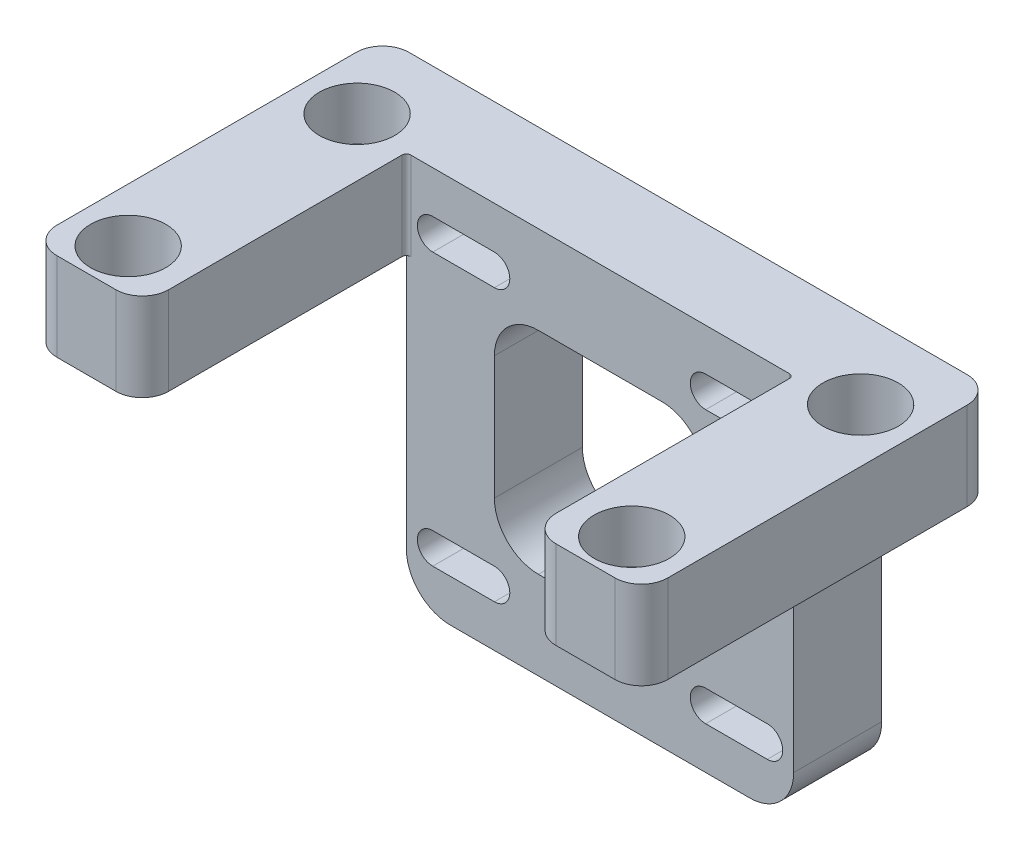
SolidWorks part; units mm, degrees
ref_plane "Front Plane" through (0, 0, 0) normal (0, 0, 1) x (1, 0, 0)
ref_plane "Top Plane" through (0, 0, 0) normal (0, 1, 0) x (1, 0, 0)
ref_plane "Right Plane" through (0, 0, 0) normal (1, 0, 0) x (0, 0, -1)
sketch "Sketch1" plane through (0, 0, 0) normal (0, 0, 1) x (1, 0, 0)
  line L0 (-19, 15.45) -> (-10.25, 15.45) construction
  line L1 (-22, 22) -> (22, 22)
  line L2 (-22, 22) -> (-22, -22)
  line L3 (-22, -22) -> (22, -22)
  line L4 (22, 22) -> (22, -22)
  line L5 (-22, 22) -> (22, -22) construction
  line L6 (-22, -22) -> (22, 22) construction
  line L7 (7, 12) -> (-7, 12)
  line L8 (12, 7) -> (12, -7)
  line L9 (7, -12) -> (-7, -12)
  line L10 (-12, 7) -> (-12, -7)
  line L11 (12, 12) -> (-12, -12) construction
  line L12 (12, -12) -> (-12, 12) construction
  line L13 (-19, 17.2) -> (-12, 17.2)
  line L14 (-19, 13.7) -> (-12, 13.7)
  line L15 (0, 0) -> (50000, 0) construction
  line L16 (-19, -17.2) -> (-12, -17.2)
  line L19 (12, 17.2) -> (19, 17.2)
  line L20 (12, 13.7) -> (19, 13.7)
  line L21 (10.25, 15.45) -> (19, 15.45) construction
  line L22 (-19, -13.7) -> (-12, -13.7)
  line L23 (12, -13.7) -> (19, -13.7)
  line L24 (12, -17.2) -> (19, -17.2)
  arc A0 (-12, -7) -> (-7, -12) centre (-7, -7) ccw
  arc A1 (7, -12) -> (12, -7) centre (7, -7) ccw
  arc A2 (12, 7) -> (7, 12) centre (7, 7) ccw
  arc A3 (-7, 12) -> (-12, 7) centre (-7, 7) ccw
  arc A4 (-19, 17.2) -> (-19, 13.7) centre (-19, 15.45) ccw
  arc A5 (19, 13.7) -> (19, 17.2) centre (19, 15.45) ccw
  circle A8 centre (0, 0) radius 12 construction
  arc A9 (12, 17.2) -> (12, 13.7) centre (12, 15.45) ccw
  arc A10 (-12, 17.2) -> (-12, 13.7) centre (-12, 15.45) cw
  arc A11 (-19, -17.2) -> (-19, -13.7) centre (-19, -15.45) cw
  arc A12 (-12, -17.2) -> (-12, -13.7) centre (-12, -15.45) ccw
  arc A13 (12, -17.2) -> (12, -13.7) centre (12, -15.45) cw
  arc A14 (19, -13.7) -> (19, -17.2) centre (19, -15.45) cw
  point P0 (0, 0)
  point P6 (0, 0)
  dimension "D4" = 5
  dimension "D9" = 1.75
  dimension "D1" = 44
  dimension "D2" = 44
  dimension "D3" = 24
  dimension "D5" = 38
  dimension "D6" = 1.75
  dimension "D7" = 15.45
  dimension "D8" = 7
extrude "Boss-Extrude1" add sketch "Sketch1" along normal blind 10
sketch "Sketch2" plane through (22, 0, 0) normal (1, 0, 0) x (0, 0, -1)
  line L0 (0, 12) -> (-40, 12)
  line L1 (0, -22) -> (0, 22) construction
  line L2 (0, 12) -> (0, 22)
  line L3 (0, 22) -> (-10, 22)
  line L4 (-40, 12) -> (-40, 16)
  line L5 (-40, 16) -> (0, 16) construction
  line L6 (-10, 22) -> (-40, 22)
  line L7 (-40, 22) -> (-40, 16)
  dimension "D1" = 4
  dimension "D2" = 40
  dimension "D3" = 12
extrude "Boss-Extrude2" add sketch "Sketch2" along normal blind 12.7
sketch "Sketch3" plane through (0, 12, 0) normal (0, -1, 0) x (1, 0, 0)
  line L0 (34.7, 0) -> (22, 0) construction
  line L1 (34.7, 40) -> (34.7, 0) construction
  line L2 (34.7, 40) -> (22, 40) construction
  circle A0 centre (28.6, 35) radius 2.6
  circle A1 centre (28.6, 9) radius 2.6
  dimension "D2" = 5.2
  dimension "D1" = 6.1
  dimension "D3" = 5
  dimension "D4" = 9
extrude "Cut-Extrude1" cut sketch "Sketch3" against normal through all
ref_plane "Plane1" through (0, 16, 0) normal (0, -1, 0) x (-1, 0, 0)
sketch "Sketch4" plane through (0, 16, 0) normal (0, -1, 0) x (-1, 0, 0)
  circle A0 centre (-28.6, -9) radius 4.275
  circle A1 centre (-28.6, -35) radius 4.275
  dimension "D1" = 8.55
  dimension "D2" = 8.55
extrude "Cut-Extrude2" cut sketch "Sketch4" against normal through all
ref_plane "Plane2" through (0, 0, 0) normal (1, 0, 0) x (0, 0, -1)
mirror "Mirror1" about plane through (0, 0, 0) normal (1, 0, 0) of "Cut-Extrude1", "Boss-Extrude2", "Cut-Extrude2"
fillet "Fillet1" radius 3 6 edges at (34.7, 17, 0) (34.7, 17, 40) (-34.7, 17, 0) (-34.7, 17, 40) (-22, 17, 40) (22, 17, 40)
fillet "Fillet2" radius 5 2 edges at (22, -22, 5) (-22, -22, 5)
fillet "Fillet3" radius 0.5 2 edges at (-22, 17, 10) (22, 17, 10)
